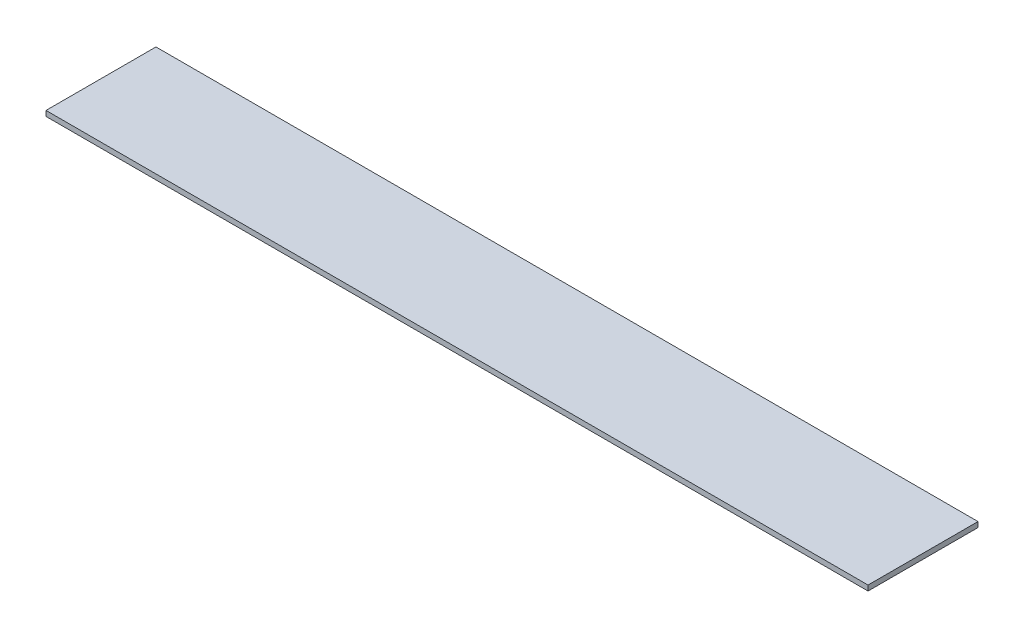
SolidWorks part; units mm, degrees
ref_plane "前视基准面" through (0, 0, 0) normal (0, 0, 1) x (1, 0, 0)
ref_plane "上视基准面" through (0, 0, 0) normal (0, 1, 0) x (1, 0, 0)
ref_plane "右视基准面" through (0, 0, 0) normal (1, 0, 0) x (0, 0, -1)
sketch "草图1" plane through (0, 0, 0) normal (0, 1, 0) x (1, 0, 0)
  line L0 (0, 0) -> (-157, 0)
  line L1 (-157, 0) -> (-157, 21)
  line L2 (-157, 21) -> (0, 21)
  line L3 (0, 21) -> (0, 0)
  line L4 (-45, 21) -> (-45, 0) construction
  line L5 (-112, 21) -> (-112, 0) construction
  line L6 (-170.4744, 10.5) -> (3.2411, 10.5) construction
  circle A0 centre (-68.5, 10.5) radius 4.5
  circle A1 centre (-147, 10.5) radius 4.5
  text T0 "压住此线弯折" font "汉仪长仿宋体" height 3
  point P16 (-10, 10.5)
  dimension "D5" = 9
  dimension "D8" = 9
  dimension "D1" = 21
  dimension "D2" = 45
  dimension "D3" = 45
  dimension "D4" = 67
  dimension "D6" = 10.5
  dimension "D7" = 23.5
  dimension "D9" = 10
  dimension "D10" = 10
extrude "凸台-拉伸1" add sketch "草图1" along normal blind 1 contours L0 L1 L2 L3
